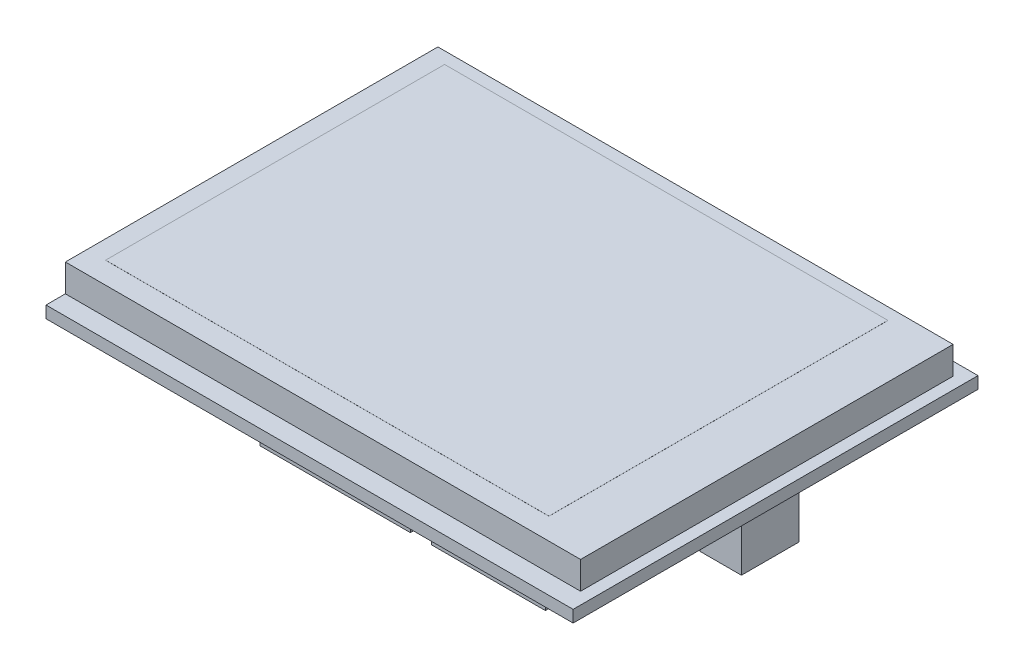
SolidWorks part; units mm, degrees
ref_plane "Front Plane" through (0, 0, 0) normal (0, 0, 1) x (1, 0, 0)
ref_plane "Top Plane" through (0, 0, 0) normal (0, 1, 0) x (1, 0, 0)
ref_plane "Right Plane" through (0, 0, 0) normal (1, 0, 0) x (0, 0, -1)
sketch "Sketch1" plane through (0, 0, 0) normal (0, 1, 0) x (1, 0, 0)
  line L1 (0, 0) -> (70.75, 0)
  line L2 (0, 0) -> (0, 54.34)
  line L3 (0, 54.34) -> (70.75, 54.34)
  line L4 (70.75, 0) -> (70.75, 54.34)
  dimension "D1" = 54.34
  dimension "D2" = 70.75
extrude "PCB" add sketch "Sketch1" along normal blind 1.6
sketch "Sketch2" plane through (0, 1.6, 0) normal (0, 1, 0) x (1, 0, 0)
  line L0 (0, 54.34) -> (0, 0) construction
  line L1 (0, 2.6) -> (69.15, 2.6)
  line L2 (0, 2.6) -> (0, 52.6)
  line L3 (0, 52.6) -> (69.15, 52.6)
  line L4 (69.15, 2.6) -> (69.15, 52.6)
  line L5 (0, 0) -> (70.75, 0) construction
  line L6 (70.75, 0) -> (70.75, 54.34) construction
  dimension "D1" = 50
  dimension "D2" = 2.6
  dimension "D3" = 1.6
extrude "Screen" add sketch "Sketch2" along normal blind 3.7
sketch "Sketch3" plane through (0, 5.3, 0) normal (0, 1, 0) x (1, 0, 0)
  line L1 (2.5, 51) -> (62, 51)
  line L2 (2.5, 51) -> (2.5, 5.5)
  line L3 (2.5, 5.5) -> (62, 5.5)
  line L4 (62, 51) -> (62, 5.5)
  dimension "D1" = 59.5
  dimension "D2" = 45.5
  dimension "D3" = 5.5
  dimension "D4" = 2.5
extrude "usable space" add sketch "Sketch3" along normal blind 0.01
sketch "Sketch4" plane through (0, 0, 0) normal (0, -1, 0) x (1, 0, 0)
  line L0 (0, -54.34) -> (0, 0) construction
  line L1 (16.8235, -15.6656) -> (0, -15.6656)
  line L2 (16.8235, -15.6656) -> (16.8235, -29.9715)
  line L3 (16.8235, -29.9715) -> (0, -29.9715)
  line L4 (0, -15.6656) -> (0, -29.9715)
  line L5 (70.75, -54.34) -> (0, -54.34) construction
  dimension "D1" = 24.3685
  dimension "D2" = 14.3059
extrude "SD slot" add sketch "Sketch4" along normal blind 2.8
sketch "Sketch6" plane through (0, 0, 0) normal (0, -1, 0) x (1, 0, 0)
  line L0 (70.75, -54.34) -> (0, -54.34) construction
  line L1 (2.2805, -47.9628) -> (8.8054, -47.9628)
  line L2 (2.2805, -47.9628) -> (2.2805, -54.34)
  line L3 (2.2805, -54.34) -> (8.8054, -54.34)
  line L4 (8.8054, -47.9628) -> (8.8054, -54.34)
  dimension "D1" = 6.3772
extrude "reset button" add sketch "Sketch6" along normal blind 2.19
sketch "Sketch7" plane through (0, -2.19, 0) normal (0, -1, 0) x (1, 0, 0)
  line L0 (2.2805, -51.1514) -> (8.8054, -51.1514) construction
  line L1 (2.2805, -47.9628) -> (2.2805, -54.34) construction
  line L2 (8.8054, -54.34) -> (8.8054, -47.9628) construction
  line L3 (5.5429, -54.34) -> (5.5429, -47.9628)
  line L4 (8.8054, -47.9628) -> (2.2805, -47.9628) construction
  circle A0 centre (5.5429, -51.1514) radius 1.58
  point P11 (5.5429, -51.1514)
  dimension "D1" = 3.16
extrude "Boss-Extrude6" add sketch "Sketch7" along normal blind 1.23 contours A0 L0 L3 | L3 L0 A0 | L0 L3 A0 | L0 A0 L3
sketch "Sketch8" plane through (0, 0, 0) normal (0, -1, 0) x (1, 0, 0)
  line L0 (70.75, -54.34) -> (8.8054, -54.34) construction
  line L1 (63.1906, -24.603) -> (68.7353, -24.603)
  line L2 (63.1906, -24.603) -> (63.1906, -32.34)
  line L3 (63.1906, -32.34) -> (68.7353, -32.34)
  line L4 (68.7353, -24.603) -> (68.7353, -32.34)
  line L5 (0, 0) -> (70.75, 0) construction
  dimension "D1" = 22
  dimension "D2" = 24.603
extrude "Boss-Extrude7" add sketch "Sketch8" along normal blind 7.75
sketch "Sketch9" plane through (0, 0, 0) normal (0, -1, 0) x (1, 0, 0)
  line L1 (27.0072, -1.7391) -> (47.1627, -1.7391)
  line L2 (27.0072, -1.7391) -> (27.0072, -4.2859)
  line L3 (27.0072, -4.2859) -> (47.1627, -4.2859)
  line L4 (47.1627, -1.7391) -> (47.1627, -4.2859)
  line L5 (50.0005, -1.7391) -> (65.2808, -1.7391)
  line L6 (50.0005, -1.7391) -> (50.0005, -4.2859)
  line L7 (50.0005, -4.2859) -> (65.2808, -4.2859)
  line L8 (65.2808, -1.7391) -> (65.2808, -4.2859)
  line L9 (17.9117, -50.3452) -> (43.2335, -50.3452)
  line L10 (17.9117, -50.3452) -> (17.9117, -53.183)
  line L11 (17.9117, -53.183) -> (43.2335, -53.183)
  line L12 (43.2335, -50.3452) -> (43.2335, -53.183)
  line L13 (45.0526, -50.3452) -> (65.7902, -50.3452)
  line L14 (45.0526, -50.3452) -> (45.0526, -53.183)
  line L15 (45.0526, -53.183) -> (65.7902, -53.183)
  line L16 (65.7902, -50.3452) -> (65.7902, -53.183)
  dimension "D1" = 27.0072
extrude "pins" add sketch "Sketch9" along normal blind 2.15
